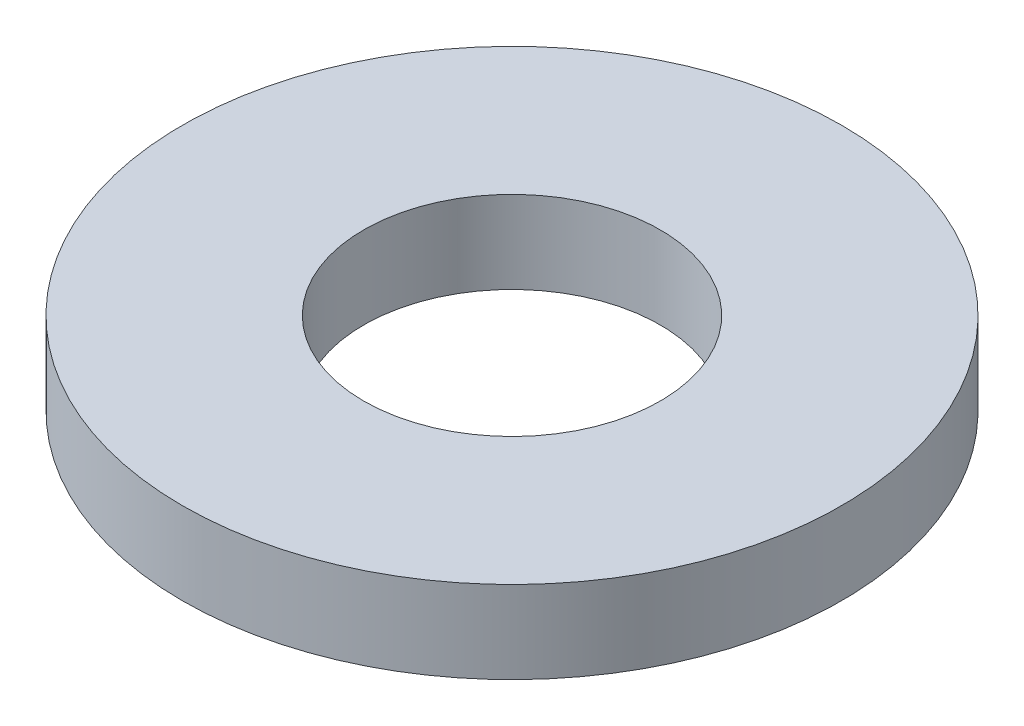
SolidWorks part; units mm, degrees
ref_plane "Front Plane" through (0, 0, 0) normal (0, 0, 1) x (1, 0, 0)
ref_plane "Top Plane" through (0, 0, 0) normal (0, 1, 0) x (1, 0, 0)
ref_plane "Right Plane" through (0, 0, 0) normal (1, 0, 0) x (0, 0, -1)
sketch "Sketch1" plane through (0, 0, 0) normal (0, 1, 0) x (1, 0, 0)
  circle A0 centre (0, 0) radius 1.8
  circle A1 centre (0, 0) radius 4
  dimension "D1" = 8
  dimension "D2" = 3.6
extrude "Boss-Extrude1" add sketch "Sketch1" along normal blind 1
